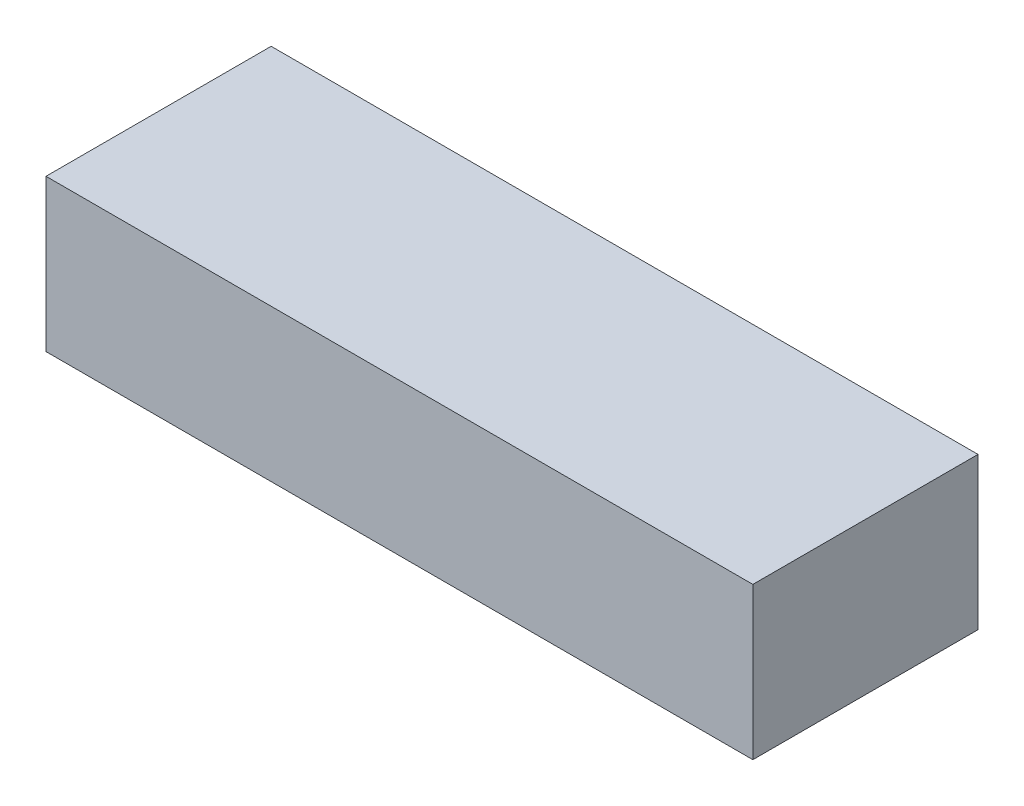
SolidWorks part; units mm, degrees
ref_plane "Front Plane" through (0, 0, 0) normal (0, 0, 1) x (1, 0, 0)
ref_plane "Top Plane" through (0, 0, 0) normal (0, 1, 0) x (1, 0, 0)
ref_plane "Right Plane" through (0, 0, 0) normal (1, 0, 0) x (0, 0, -1)
sketch "Sketch1" plane through (0, 0, 0) normal (0, 1, 0) x (1, 0, 0)
  line L1 (-67.5, -21.5) -> (67.5, -21.5)
  line L2 (-67.5, -21.5) -> (-67.5, 21.5)
  line L3 (-67.5, 21.5) -> (67.5, 21.5)
  line L4 (67.5, -21.5) -> (67.5, 21.5)
  line L5 (-67.5, -21.5) -> (67.5, 21.5) construction
  line L6 (-67.5, 21.5) -> (67.5, -21.5) construction
  point P0 (0, 0)
  dimension "D1" = 43
  dimension "D2" = 135
extrude "Boss-Extrude1" add sketch "Sketch1" along normal blind 29
